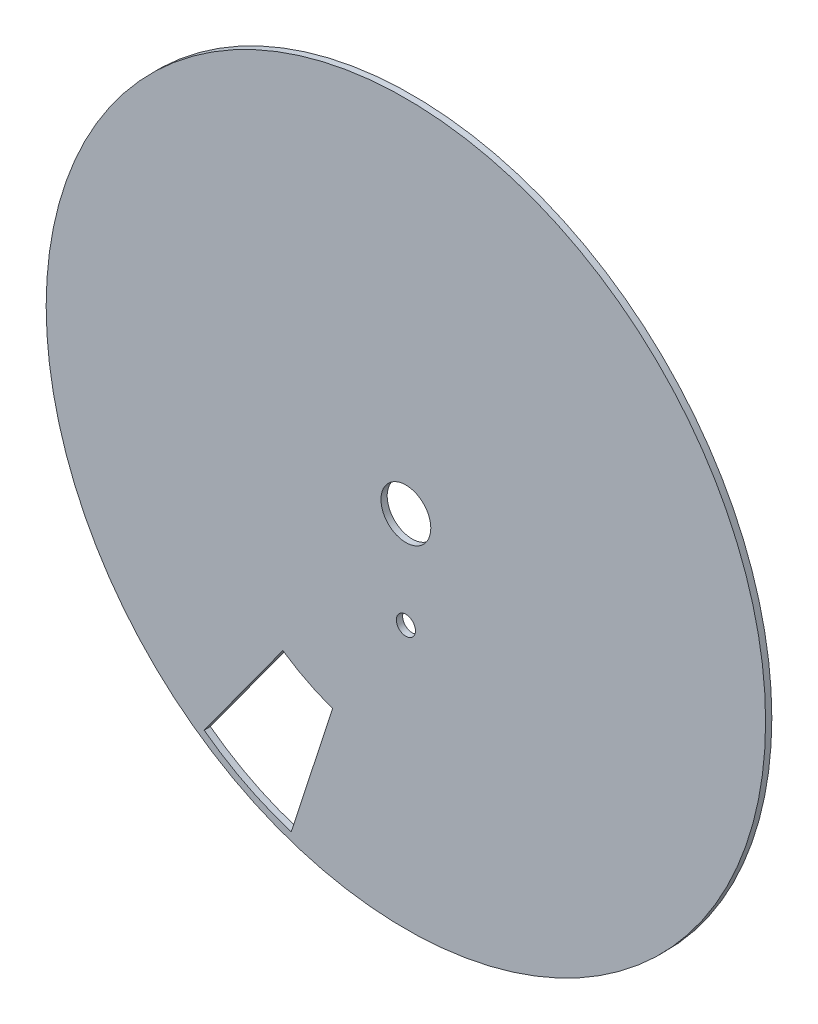
SolidWorks part; units mm, degrees
ref_plane "Plan de face" through (0, 0, 0) normal (0, 0, 1) x (1, 0, 0)
ref_plane "Plan de dessus" through (0, 0, 0) normal (0, 1, 0) x (1, 0, 0)
ref_plane "Plan de droite" through (0, 0, 0) normal (1, 0, 0) x (0, 0, -1)
sketch "Esquisse1" plane through (0, 0, 0) normal (0, 0, 1) x (1, 0, 0)
  circle A0 centre (0, 0) radius 57.75
  circle A1 centre (0, 0) radius 4
  dimension "D1" = 115.5
extrude "Boss.-Extru.1" add sketch "Esquisse1" along normal blind 1
sketch "Esquisse2" plane through (0, 0, 0) normal (0, 0, -1) x (-1, 0, 0)
  circle A0 centre (0, -15.504) radius 1.53
extrude "Enlèv. mat.-Extru.1" cut sketch "Esquisse2" against normal through all both and the other way through all
sketch "Esquisse3" plane through (0, 0, 0) normal (0, 0, -1) x (-1, 0, 0)
  line L0 (19.7551, -28.8918) -> (32.3896, -46.2818)
  line L1 (32.6896, -46.6947) -> (19.7551, -28.8918) construction
  line L2 (11.7622, -32.9644) -> (18.4052, -53.4093)
  line L3 (11.7622, -32.9644) -> (18.5623, -53.8929) construction
  arc A0 (11.7622, -32.9644) -> (19.7551, -28.8918) centre (0, 0) ccw
  arc A1 (18.4052, -53.4093) -> (32.3896, -46.2818) centre (4.7116, -9.2586) ccw
extrude "Enlèv. mat.-Extru.2" cut sketch "Esquisse3" against normal blind 1
